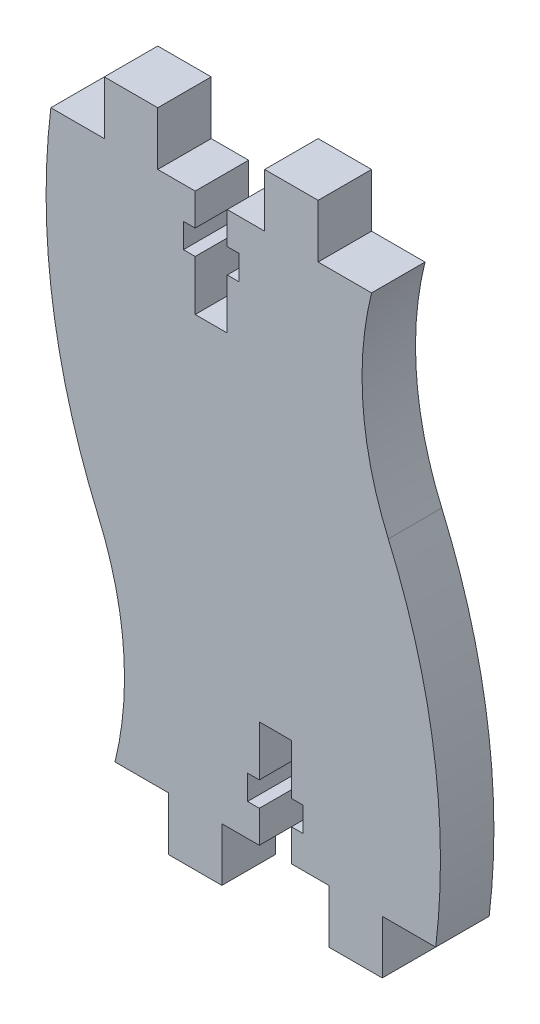
SolidWorks part; units mm, degrees
ref_plane "Front Plane" through (0, 0, 0) normal (0, 0, 1) x (1, 0, 0)
ref_plane "Top Plane" through (0, 0, 0) normal (0, 1, 0) x (1, 0, 0)
ref_plane "Right Plane" through (0, 0, 0) normal (1, 0, 0) x (0, 0, -1)
sketch "Sketch1" plane through (0, 0, 0) normal (0, 0, 1) x (1, 0, 0)
  line L1 (-5, 0) -> (25, 0) construction
  line L8 (20.5666, 30.8564) -> (-6.5666, 19.1436) construction
  line L17 (-5, 0) -> (19, 50) construction
  line L29 (14, 50) -> (19, 50)
  line L30 (-6, 50) -> (-11, 50)
  line L39 (-5, 0) -> (0, 0)
  line L51 (20, 0) -> (25, 0)
  line L52 (-11, 50) -> (-5, 0) construction
  line L53 (25, 0) -> (19, 50) construction
  arc A0 (19, 50) -> (20.5666, 30.8564) centre (48.1098, 42.7462) ccw
  arc A1 (20.5666, 30.8564) -> (25, 0) centre (-34.1098, 7.2538) cw
  arc A2 (-11, 50) -> (-6.5666, 19.1436) centre (48.1098, 42.7462) ccw
  arc A3 (-6.5666, 19.1436) -> (-5, 0) centre (-34.1098, 7.2538) cw
  point P2 (7, 25)
  point P7 (7, 25)
  point P20 (10, 0)
  line B0 (6.6, 47) -> (6.6, 44.7)
  line B1 (2.5, 44.7) -> (2.5, 40)
  line B2 (5.5, 40) -> (5.5, 44.7)
  line B3 (6.6, 44.7) -> (5.5, 44.7)
  line B4 (4, 50) -> (4, 38.7792) construction
  line B5 (5.5, 50) -> (9, 50)
  line B6 (9, 55) -> (14, 55)
  line B7 (14, 55) -> (14, 50)
  line B8 (9, 55) -> (9, 50)
  line B9 (2.5, 50) -> (-1, 50)
  line B10 (-1, 50) -> (-1, 55)
  line B11 (-1, 55) -> (-6, 55)
  line B12 (-6, 55) -> (-6, 50)
  line B13 (5.5, 50) -> (2.5, 50) construction
  line B14 (2.5, 50) -> (2.5, 47)
  line B15 (2.5, 44.7) -> (1.4, 44.7)
  line B16 (1.4, 47) -> (2.5, 47)
  line B17 (2.5, 40) -> (5.5, 40)
  line B18 (5.5, 47) -> (6.6, 47)
  line B19 (1.4, 44.7) -> (1.4, 47)
  line B20 (5.5, 47) -> (5.5, 50)
  line B21 (4, 40) -> (4, 50) construction
  line B22 (7.4, 3) -> (7.4, 5.3)
  line B23 (11.5, 5.3) -> (11.5, 10)
  line B24 (8.5, 10) -> (8.5, 5.3)
  line B25 (7.4, 5.3) -> (8.5, 5.3)
  line B26 (10, 0) -> (10, 11.2208) construction
  line B27 (8.5, 0) -> (5, 0)
  line B28 (5, -5) -> (0, -5)
  line B29 (0, -5) -> (0, 0)
  line B30 (5, -5) -> (5, 0)
  line B31 (11.5, 0) -> (15, 0)
  line B32 (15, 0) -> (15, -5)
  line B33 (15, -5) -> (20, -5)
  line B34 (20, -5) -> (20, 0)
  line B35 (8.5, 0) -> (11.5, 0) construction
  line B36 (11.5, 0) -> (11.5, 3)
  line B37 (11.5, 5.3) -> (12.6, 5.3)
  line B38 (12.6, 3) -> (11.5, 3)
  line B39 (11.5, 10) -> (8.5, 10)
  line B40 (8.5, 3) -> (7.4, 3)
  line B41 (12.6, 5.3) -> (12.6, 3)
  line B42 (8.5, 3) -> (8.5, 0)
  line B43 (10, 10) -> (10, 0) construction
  dimension "D3" = 30
  dimension "D1" = 50
  dimension "D2" = 6
  dimension "D4" = 5
sketch_block_instance "Insert M3 plots ep 5mm-1"
sketch_block "Insert M3 plots ep 5mm" parameters "D1"=10, "D2"=5, "D3"=5
sketch_block_instance "Decoupe Insert M3-4"
sketch_block "Decoupe Insert M3" parameters "D1"=5.2, "D2"=3, "D3"=2.3, "D4"=3, "D5"=10
sketch_block_instance "Insert M3 plots ep 5mm-3"
extrude "Boss-Extrude1" add sketch "Sketch1" along normal blind 5 contours B42 B40 B22 B25 B24 B39 B23 B37 B41 B38 B36 B31 B32 B33 B34 A1 A0 B7 B6 B8 B5 B20 B18 B0 B3 B2 B17 B1 B15 B19 B16 B14 B9 B10 B11 B12 A2 A3 B29 B28 B30 B27
